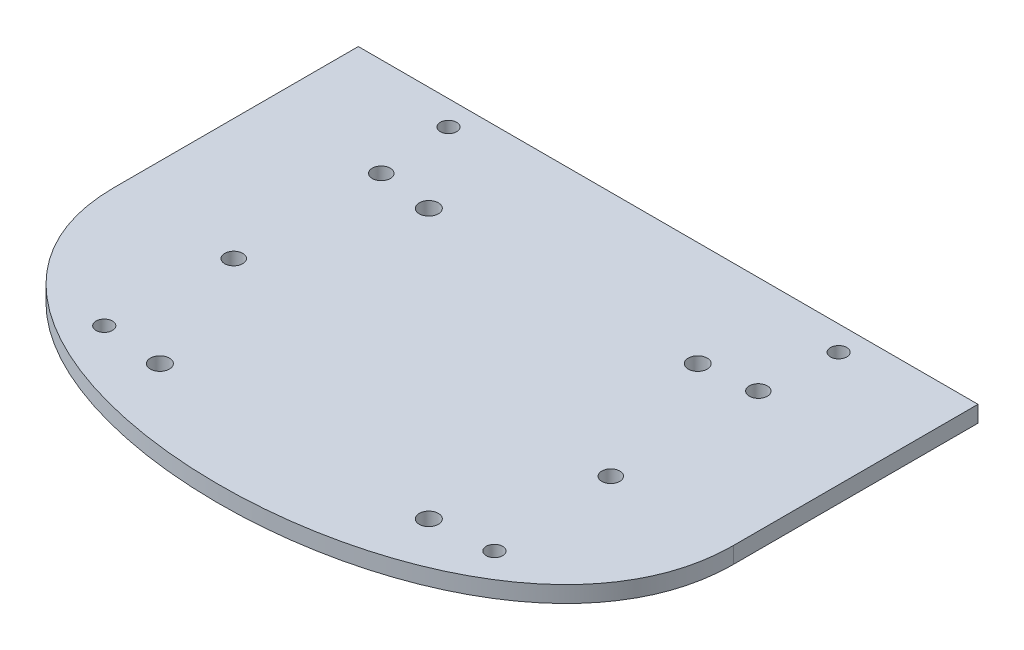
SolidWorks part; units mm, degrees
ref_plane "Front Plane" through (0, 0, 0) normal (0, 0, 1) x (1, 0, 0)
ref_plane "Top Plane" through (0, 0, 0) normal (0, 1, 0) x (1, 0, 0)
ref_plane "Right Plane" through (0, 0, 0) normal (1, 0, 0) x (0, 0, -1)
sketch "Sketch2" plane through (0, 0, 0) normal (0, 1, 0) x (1, 0, 0)
  line L4 (-48.006, -33.6908) -> (-48.006, 91.0268) construction
  line L5 (48.006, -34.798) -> (-48.006, -34.798) construction
  line L6 (48.006, -34.798) -> (48.006, 34.798) construction
  line L7 (48.006, 34.798) -> (-48.006, 34.798)
  line L8 (-48.006, -34.798) -> (-48.006, 34.798) construction
  line L9 (48.006, -34.798) -> (-48.006, 34.798) construction
  line L10 (48.006, 34.798) -> (-48.006, -34.798) construction
  line L11 (48.006, 148.5724) -> (48.006, -105.4276) construction
  line L12 (-48.006, 34.798) -> (-48.006, -3.048)
  line L13 (48.006, 34.798) -> (48.006, -3.048)
  spline S0 degree 3 poles (-48.006, -3.048) (-48.006, -45.3813) (48.006, -45.3813) (48.006, -3.048) knots 0 0 0 0 1 1 1 1
  point P0 (0, 0)
  dimension "D3" = 180
  dimension "D4" = 127
  dimension "D5" = 69.596
  dimension "D1" = 96.012
  dimension "D2" = 180
  dimension "D6" = 127
extrude "Boss-Extrude1" add sketch "Sketch2" along normal blind 2.54
sketch "Sketch3" plane through (0, 2.54, 0) normal (0, 1, 0) x (1, 0, 0)
  line L0 (0, 0) -> (0, 43.6246) construction
  line L9 (-48.006, 34.798) -> (-48.006, -3.048) construction
  line L10 (48.006, 34.798) -> (-48.006, 34.798) construction
  line L11 (-29.21, 19.558) -> (-29.21, -3.302) construction
  line L12 (29.21, 19.558) -> (29.21, -3.302) construction
  line L13 (-30.226, 30.988) -> (-30.226, -22.352) construction
  line L14 (30.226, 30.988) -> (30.226, -22.352) construction
  line L15 (0, -34.798) -> (29.21, -34.798) construction
  line L20 (20.8342, 18.5482) -> (0, -2.286) construction
  line L21 (0, -2.286) -> (29.464, -2.286) construction
  circle A2 centre (-30.226, 30.988) radius 1.27
  circle A5 centre (-30.226, -22.352) radius 1.27
  circle A6 centre (30.226, -22.352) radius 1.27
  circle A7 centre (30.226, 30.988) radius 1.27
  circle A10 centre (-29.21, 19.558) radius 1.397
  circle A11 centre (-29.21, -3.302) radius 1.397
  circle A12 centre (29.21, -3.302) radius 1.397
  circle A13 centre (29.21, 19.558) radius 1.397
  circle A15 centre (0, -2.286) radius 29.464 construction
  circle A16 centre (20.8342, 18.5482) radius 1.4804
  circle A17 centre (20.8342, -23.1202) radius 1.4804
  circle A18 centre (-20.8342, 18.5482) radius 1.4804
  circle A19 centre (-20.8342, -23.1202) radius 1.4804
  spline S0 degree 3 poles (-48.006, -3.048) (-48.006, -45.3813) (48.006, -45.3813) (48.006, -3.048) knots 0 0 0 0 1 1 1 1 construction
  text T0 "GRITSBot X" font "OLF SimpleSansOC" height in points 28
  dimension "D5" = 15.24
  dimension "D6" = 17.272
  dimension "D9" = 2.54
  dimension "D13" = 45
  dimension "D2" = 2.794
  dimension "D7" = 58.928
  dimension "D8" = 37.084
  dimension "D14" = 2.9608
  dimension "D3" = 22.86
  dimension "D4" = 29.21
  dimension "D10" = 3.81
  dimension "D11" = 17.78
  dimension "D12" = 53.34
extrude "Cut-Extrude1" cut sketch "Sketch3" against normal through all and the other way through all
